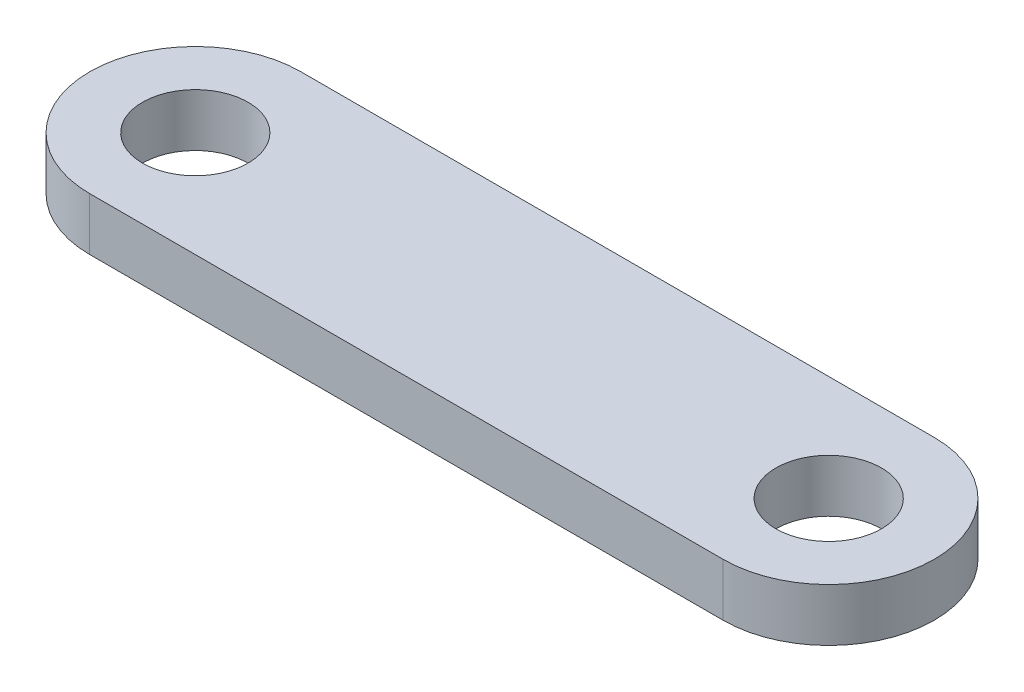
SolidWorks part; units mm, degrees
ref_plane "Front Plane" through (0, 0, 0) normal (0, 0, 1) x (1, 0, 0)
ref_plane "Top Plane" through (0, 0, 0) normal (0, 1, 0) x (1, 0, 0)
ref_plane "Right Plane" through (0, 0, 0) normal (1, 0, 0) x (0, 0, -1)
sketch "Sketch1" plane through (0, 0, 0) normal (0, 1, 0) x (1, 0, 0)
  line L0 (-72.3468, 0) -> (-12.3468, 0) construction
  line L1 (-72.3468, 10) -> (-12.3468, 10)
  line L2 (-72.3468, -10) -> (-12.3468, -10)
  arc A0 (-72.3468, 10) -> (-72.3468, -10) centre (-72.3468, 0) ccw
  arc A1 (-12.3468, -10) -> (-12.3468, 10) centre (-12.3468, 0) ccw
  circle A2 centre (-72.3468, 0) radius 5
  circle A3 centre (-12.3468, 0) radius 5
  point P3 (-42.3468, 0)
  dimension "D1" = 60
  dimension "D2" = 10
  dimension "D3" = 10
  dimension "D4" = 10
extrude "Boss-Extrude1" add sketch "Sketch1" along normal blind 5
